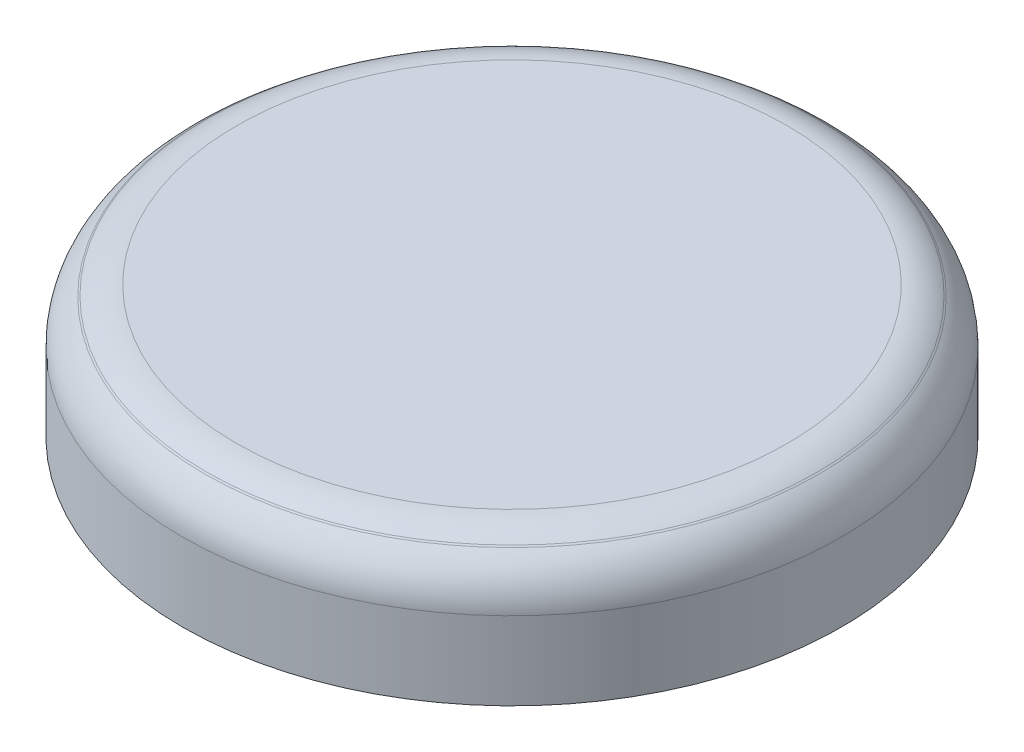
SolidWorks part; units mm, degrees
ref_plane "Front Plane" through (0, 0, 0) normal (0, 0, 1) x (1, 0, 0)
ref_plane "Top Plane" through (0, 0, 0) normal (0, 1, 0) x (1, 0, 0)
ref_plane "Right Plane" through (0, 0, 0) normal (1, 0, 0) x (0, 0, -1)
sketch "Sketch1" plane through (0, 0, 0) normal (0, 1, 0) x (1, 0, 0)
  circle A0 centre (0, 0) radius 12.5
  circle A1 centre (0, 0) radius 4.25
  dimension "D1" = 25
  dimension "D2" = 8.5
extrude "Boss-Extrude1" add sketch "Sketch1" along normal blind 5
sketch "Sketch2" plane through (0, 5, 0) normal (0, 1, 0) x (1, 0, 0)
  circle A0 centre (0, 0) radius 4.25
  circle A1 centre (0, 0) radius 4.25 construction
  dimension "D1" = 0
extrude "Boss-Extrude2" add sketch "Sketch2" against normal blind 1
sketch "Sketch3" plane through (0, 0, 0) normal (0, -1, 0) x (-1, 0, 0)
  circle A0 centre (0, 0) radius 9 construction
  circle A1 centre (0, -9) radius 1.25
  circle A2 centre (-9, 0) radius 1.25
  circle A3 centre (0, 9) radius 1.25
  circle A4 centre (9, 0) radius 1.25
  dimension "D1" = 18
  dimension "D2" = 2.5
extrude "Cut-Extrude1" cut sketch "Sketch3" against normal blind 3
chamfer "Chamfer1" distance 1 angle 55 1 edges at (0, 5, 12.5)
fillet "Fillet1" radius 2 2 edges at (0, 5, 11.0719) (0, 4, 12.5)
